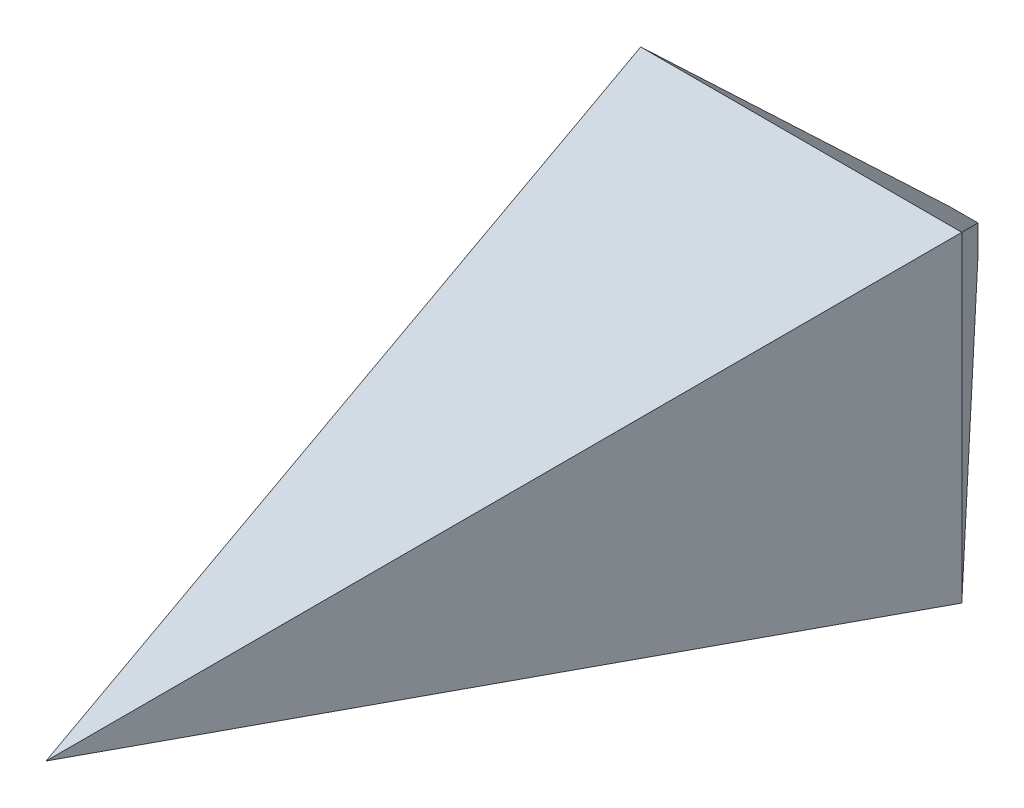
SolidWorks part; units mm, degrees
ref_plane "Front" through (0, 0, 0) normal (0, 0, 1) x (1, 0, 0)
ref_plane "Top" through (0, 0, 0) normal (0, 1, 0) x (1, 0, 0)
ref_plane "Right" through (0, 0, 0) normal (1, 0, 0) x (0, 0, -1)
other "Configuration Table"
sketch "Sketch1" plane through (0, 0, 0) normal (0, 0, 1) x (1, 0, 0)
  line L0 (37.5, -37.5) -> (-37.5, 37.5) construction
  line L1 (37.5, 37.5) -> (-37.5, 37.5)
  line L2 (37.5, 37.5) -> (37.5, -37.5)
  line L3 (37.5, -37.5) -> (-37.5, -37.5)
  line L4 (-37.5, 37.5) -> (-37.5, -37.5)
  dimension "D1" = 75
extrude "Extrude1" add sketch "Sketch1" along normal blind 181 draft 12
sketch "Sketch2" plane through (0, 0, 0) normal (0, 0, 1) x (1, 0, 0)
  line L4 (37.5, -37.5) -> (37.5, 37.5)
  line L5 (-37.5, -37.5) -> (37.5, -37.5)
  line L6 (-37.5, 37.5) -> (-37.5, -37.5)
  line L7 (37.5, 37.5) -> (-37.5, 37.5)
  line L8 (37.5, -37.5) -> (37.5, 37.5)
  line L9 (-37.5, -37.5) -> (37.5, -37.5)
  line L10 (-37.5, 37.5) -> (-37.5, -37.5)
  line L11 (37.5, 37.5) -> (-37.5, 37.5)
  dimension "D1" = 0
extrude "Extrude2" add sketch "Sketch2" against normal blind 38 draft 42
